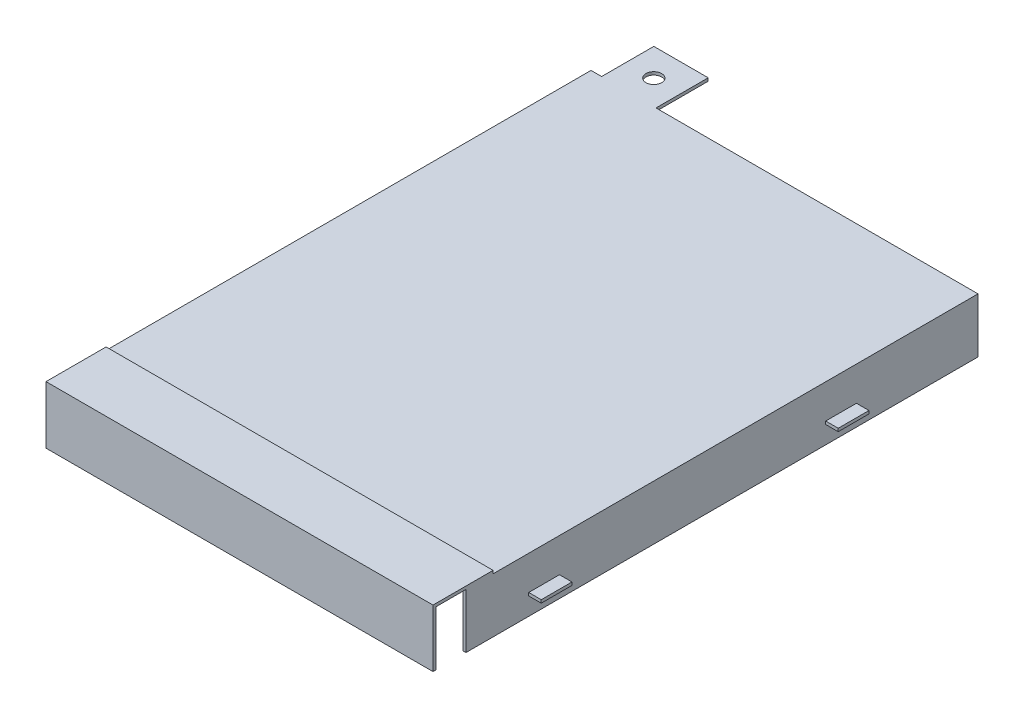
SolidWorks part; units mm, degrees
ref_plane "Спереди" through (0, 0, 0) normal (0, 0, 1) x (1, 0, 0)
ref_plane "Сверху" through (0, 0, 0) normal (0, 1, 0) x (1, 0, 0)
ref_plane "Справа" through (0, 0, 0) normal (1, 0, 0) x (0, 0, -1)
sketch "Эскиз1" plane through (0, 0, 0) normal (0, 1, 0) x (1, 0, 0)
  line L0 (0, 0) -> (-38577.3156, 0) construction
  line L1 (0, 0) -> (0, 38577.3156) construction
  line L3 (35.575, 47.075) -> (-35.575, 47.075)
  line L4 (35.575, 47.075) -> (35.575, -47.075)
  line L5 (35.575, -47.075) -> (-35.575, -47.075)
  line L6 (-35.575, 47.075) -> (-35.575, -47.075)
  line L7 (35.575, 47.075) -> (-35.575, -47.075) construction
  line L8 (35.575, -47.075) -> (-35.575, 47.075) construction
  point P5 (0, 0)
  dimension "D1" = 71.15
  dimension "D2" = 94.15
extrude "Бобышка-Вытянуть1" add sketch "Эскиз1" along normal blind 0.55
sketch "Эскиз2" plane through (0, 0, 0) normal (0, -1, 0) x (1, 0, 0)
  line L0 (35.575, -47.075) -> (-35.575, -47.075) construction
  line L1 (-35.575, 47.075) -> (-35.025, 47.075)
  line L2 (-35.575, 47.075) -> (-35.575, -47.075)
  line L3 (-35.575, -47.075) -> (-35.025, -47.075)
  line L4 (-35.025, 47.075) -> (-35.025, -47.075)
  line L6 (35.575, 47.075) -> (35.025, 47.075)
  line L7 (35.575, 47.075) -> (35.575, -47.075)
  line L8 (35.575, -47.075) -> (35.025, -47.075)
  line L9 (35.025, 47.075) -> (35.025, -47.075)
  dimension "D1" = 0.55
extrude "Бобышка-Вытянуть2" add sketch "Эскиз2" along normal blind 9.5
sketch "Эскиз3" plane through (0, 0.55, 0) normal (0, 1, 0) x (1, 0, 0)
  line L0 (35.575, 47.075) -> (-35.575, 47.075) construction
  line L1 (-33.625, 47.075) -> (-23.625, 47.075)
  line L2 (-33.625, 47.075) -> (-33.625, 56.675)
  line L3 (-33.625, 56.675) -> (-23.625, 56.675)
  line L4 (-23.625, 47.075) -> (-23.625, 56.675)
  line L5 (-35.575, 47.075) -> (-35.575, -47.075) construction
  dimension "D1" = 10
  dimension "D2" = 9.6
  dimension "D3" = 1.95
extrude "Бобышка-Вытянуть3" add sketch "Эскиз3" against normal up to surface (0.55 mm away) up to face at (0, 0, 0)
sketch "Эскиз4" plane through (0, 0.55, 0) normal (0, 1, 0) x (1, 0, 0)
  line L2 (-23.625, 47.075) -> (-23.625, 56.675) construction
  line L3 (-23.625, 56.675) -> (-33.625, 56.675) construction
  circle A0 centre (-28.575, 51.625) radius 1.45
  dimension "D1" = 2.9
  dimension "D2" = 3.5
  dimension "D3" = 3.6
extrude "Вырез-Вытянуть1" cut sketch "Эскиз4" against normal up to surface (0.55 mm away) up to face at (-14.3125, 0, -25.9375)
sketch "Эскиз5" plane through (-35.575, 0, 0) normal (-1, 0, 0) x (0, 0, 1)
  line L0 (42.075, 0.55) -> (42.075, 1.1)
  line L1 (-47.075, 0.55) -> (47.075, 0.55) construction
  line L2 (42.075, 1.1) -> (53.125, 1.1)
  line L3 (53.125, 1.1) -> (53.125, -9.5)
  line L4 (53.125, -9.5) -> (52.575, -9.5)
  line L5 (52.575, -9.5) -> (52.575, 0.55)
  line L6 (52.575, 0.55) -> (42.075, 0.55)
  line L7 (47.075, -9.5) -> (-47.075, -9.5) construction
  line L8 (47.075, 0.55) -> (47.075, -9.5) construction
  dimension "D1" = 0.55
  dimension "D2" = 5.5
  dimension "D3" = 5
extrude "Бобышка-Вытянуть4" add sketch "Эскиз5" against normal up to surface (71.15 mm away) up to face at (35.575, -4.475, 0)
sketch "Эскиз6" plane through (-35.575, 0, 0) normal (-1, 0, 0) x (0, 0, 1)
  line L0 (47.075, -9.5) -> (-47.075, -9.5) construction
  line L1 (-24.725, -5.7) -> (-19.075, -5.7)
  line L2 (-24.725, -5.7) -> (-24.725, -6.25)
  line L3 (-24.725, -6.25) -> (-19.075, -6.25)
  line L4 (-19.075, -5.7) -> (-19.075, -6.25)
  line L5 (-47.075, 0.55) -> (-47.075, -9.5) construction
  line L7 (29.875, -5.7) -> (35.525, -5.7)
  line L8 (29.875, -5.7) -> (29.875, -6.25)
  line L9 (29.875, -6.25) -> (35.525, -6.25)
  line L10 (35.525, -5.7) -> (35.525, -6.25)
  dimension "D1" = 0.55
  dimension "D2" = 5.65
  dimension "D3" = 3.8
  dimension "D4" = 28
  dimension "D5" = 60.25
extrude "Бобышка-Вытянуть5" add sketch "Эскиз6" along normal blind 2.3
mirror "Зеркальное отражение1" about plane through (0, 0, 0) normal (1, 0, 0) of "Бобышка-Вытянуть5"
